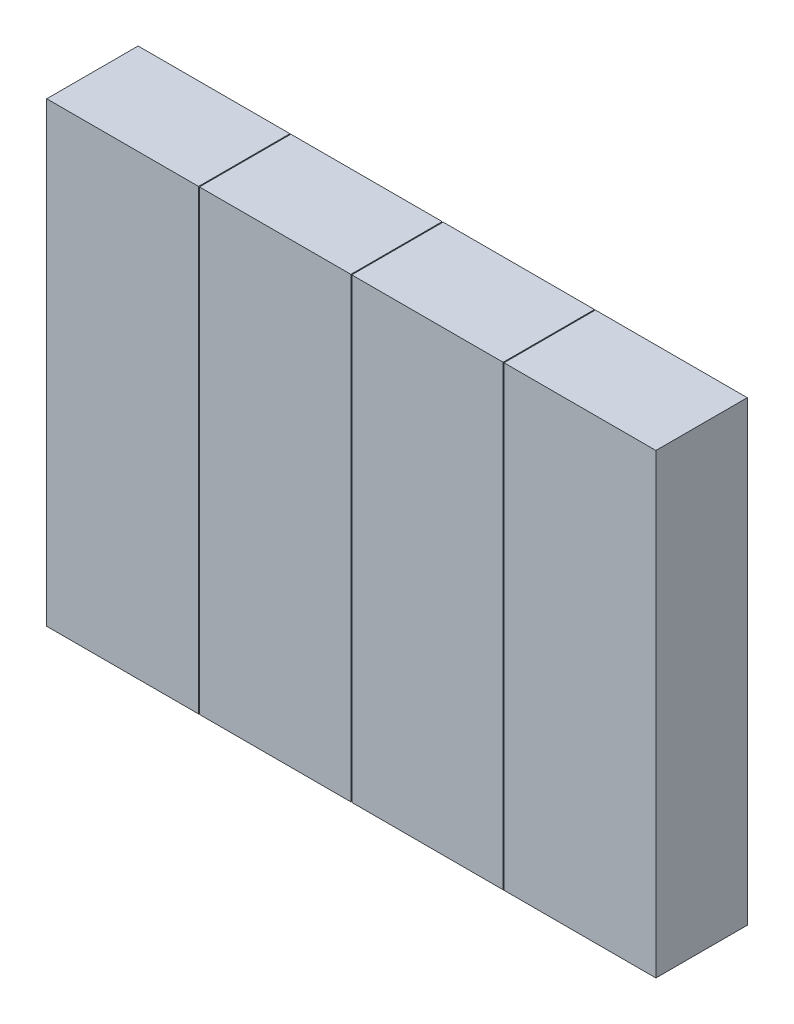
SolidWorks part; units mm, degrees
ref_plane "Front Plane" through (0, 0, 0) normal (0, 0, 1) x (1, 0, 0)
ref_plane "Top Plane" through (0, 0, 0) normal (0, 1, 0) x (1, 0, 0)
ref_plane "Right Plane" through (0, 0, 0) normal (1, 0, 0) x (0, 0, -1)
sketch "Sketch1" plane through (0, 0, 0) normal (0, 0, 1) x (1, 0, 0)
  line L1 (83.3371, 157.8213) -> (-116.6629, 157.8213)
  line L2 (83.3371, 157.8213) -> (83.3371, 307.8213)
  line L3 (83.3371, 307.8213) -> (-116.6629, 307.8213)
  line L4 (-116.6629, 157.8213) -> (-116.6629, 307.8213)
  dimension "D1" = 150
  dimension "D2" = 200
extrude "Boss-Extrude1" add sketch "Sketch1" along normal blind 30
sketch "Sketch2" plane through (0, 0, 30) normal (0, 0, 1) x (1, 0, 0)
  line L0 (83.3371, 307.8213) -> (-116.6629, 307.8213) construction
  line L1 (-66.8129, 307.8213) -> (-66.5129, 307.8213)
  line L2 (-66.8129, 307.8213) -> (-66.8129, 157.8213)
  line L3 (-66.8129, 157.8213) -> (-66.5129, 157.8213)
  line L4 (-66.5129, 307.8213) -> (-66.5129, 157.8213)
  line L5 (-116.6629, 157.8213) -> (83.3371, 157.8213) construction
  line L6 (-116.6629, 307.8213) -> (-116.6629, 157.8213) construction
  line L7 (-16.8129, 307.8213) -> (-16.8129, 157.8213)
  line L8 (-16.5129, 307.8213) -> (-16.5129, 157.8213)
  line L9 (-16.8129, 307.8213) -> (-16.5129, 307.8213)
  line L10 (-16.8129, 157.8213) -> (-16.5129, 157.8213)
  line L11 (33.1871, 307.8213) -> (33.1871, 157.8213)
  line L12 (33.4871, 307.8213) -> (33.4871, 157.8213)
  line L13 (33.1871, 307.8213) -> (33.4871, 307.8213)
  line L14 (33.1871, 157.8213) -> (33.4871, 157.8213)
  dimension "D1" = 0.3
  dimension "D2" = 49.85
  dimension "D3" = 3
extrude "Cut-Extrude1" cut sketch "Sketch2" against normal through all
